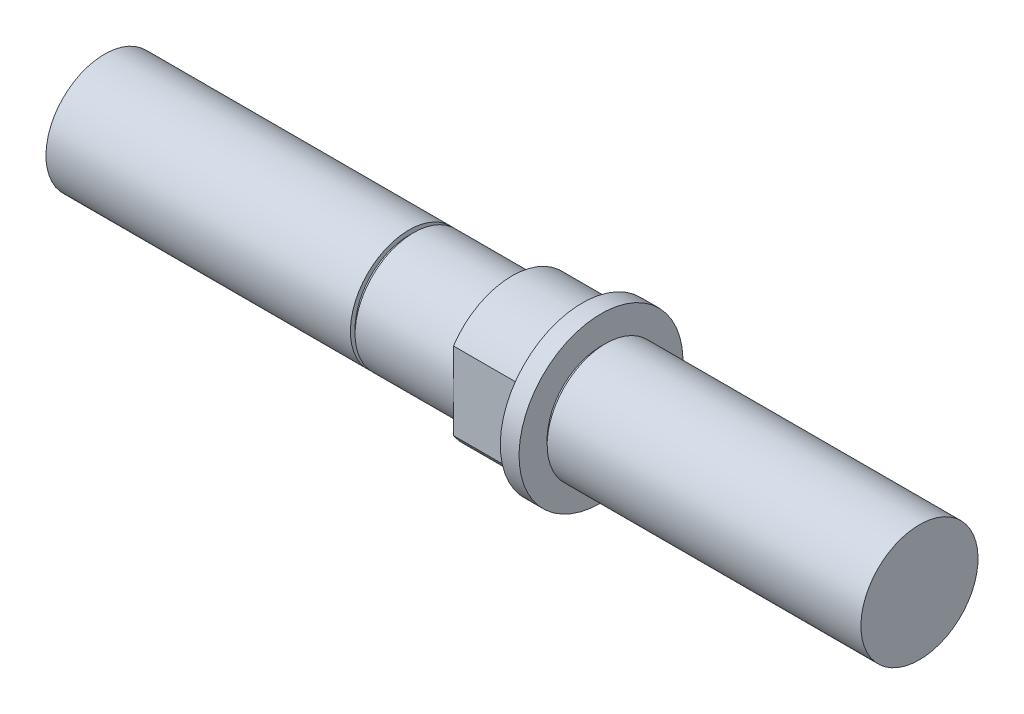
SolidWorks part; units mm, degrees
material "Alloy Steel"
ref_plane "Front Plane" through (0, 0, 0) normal (0, 0, 1) x (1, 0, 0)
ref_plane "Top Plane" through (0, 0, 0) normal (0, 1, 0) x (1, 0, 0)
ref_plane "Right Plane" through (0, 0, 0) normal (1, 0, 0) x (0, 0, -1)
sketch "Sketch2" plane through (0, 0, 0) normal (0, 0, 1) x (1, 0, 0)
  line L0 (0, 0) -> (0, 12.5)
  line L1 (0, 12.5) -> (-68, 12.5)
  line L2 (-68, 12.5) -> (-68, 17.5)
  line L3 (-68, 17.5) -> (-72, 17.5)
  line L4 (-72, 17.5) -> (-72, 15)
  line L6 (-174, 12.5) -> (-174, 0)
  line L7 (-174, 0) -> (0, 0) construction
  line L8 (-72, 15) -> (-87, 15)
  line L9 (-87, 15) -> (-87, 12.5)
  line L10 (-87, 12.5) -> (-174, 12.5)
  line L11 (0, 0) -> (-174, 0) construction
  line L12 (0, 0) -> (-174, 0)
  dimension "D1" = 12.5
  dimension "D2" = 17.5
  dimension "D3" = 15
  dimension "D4" = 12.5
  dimension "D5" = 4
  dimension "D6" = 15
  dimension "D7" = 87
  dimension "D8" = 68
revolve "Revolve1" add sketch "Sketch2" angle 360 about L7
sketch "Sketch3" plane through (0, 0, 0) normal (0, 0, 1) x (1, 0, 0)
  line L0 (-68, 12.5) -> (-67, 12.5)
  line L1 (0, 12.5) -> (-68, 12.5) construction
  line L2 (-67, 12.5) -> (-67, 11.5)
  line L3 (-67, 11.5) -> (-68, 11.5)
  line L4 (-68, -17.5) -> (-68, 17.5) construction
  line L5 (-68, 11.5) -> (-68, 12.5)
  line L6 (0, 0) -> (-136.977, 0) construction
  line L13 (-174, 12.5) -> (-174, -12.5) construction
  line L14 (-87, 12.5) -> (-174, 12.5) construction
  line L15 (-109, 12.5) -> (-108, 12.5)
  line L16 (-108, 12.5) -> (-108, 11.5)
  line L17 (-108, 11.5) -> (-109, 11.5)
  line L18 (-109, 11.5) -> (-109, 12.5)
  dimension "D1" = 1
  dimension "D2" = 1
  dimension "D3" = 11.5
  dimension "D4" = 11.5
  dimension "D5" = 65
revolve "Cut-Revolve1" cut sketch "Sketch3" angle 360 about L6
sketch "Sketch5" plane through (-87, 0, 0) normal (-1, 0, 0) x (0, 0, 1)
  line L0 (0, 0) -> (0, -12.5) construction
  line L3 (-12.5, 8.2916) -> (-12.5, -8.2916)
  line L4 (12.5, 8.2916) -> (12.5, -8.2916)
  circle A0 centre (0, 0) radius 12.5 construction
  arc A1 (-12.5, -8.2916) -> (12.5, -8.2916) centre (0, 0) ccw
  arc A2 (12.5, 8.2916) -> (-12.5, 8.2916) centre (0, 0) ccw
  dimension "D2" = 15
  dimension "D1" = 25
extrude "Cut-Extrude1" cut sketch "Sketch5" against normal up to surface (15 mm away) flip side to cut up to face at (-72, -15, 0)
